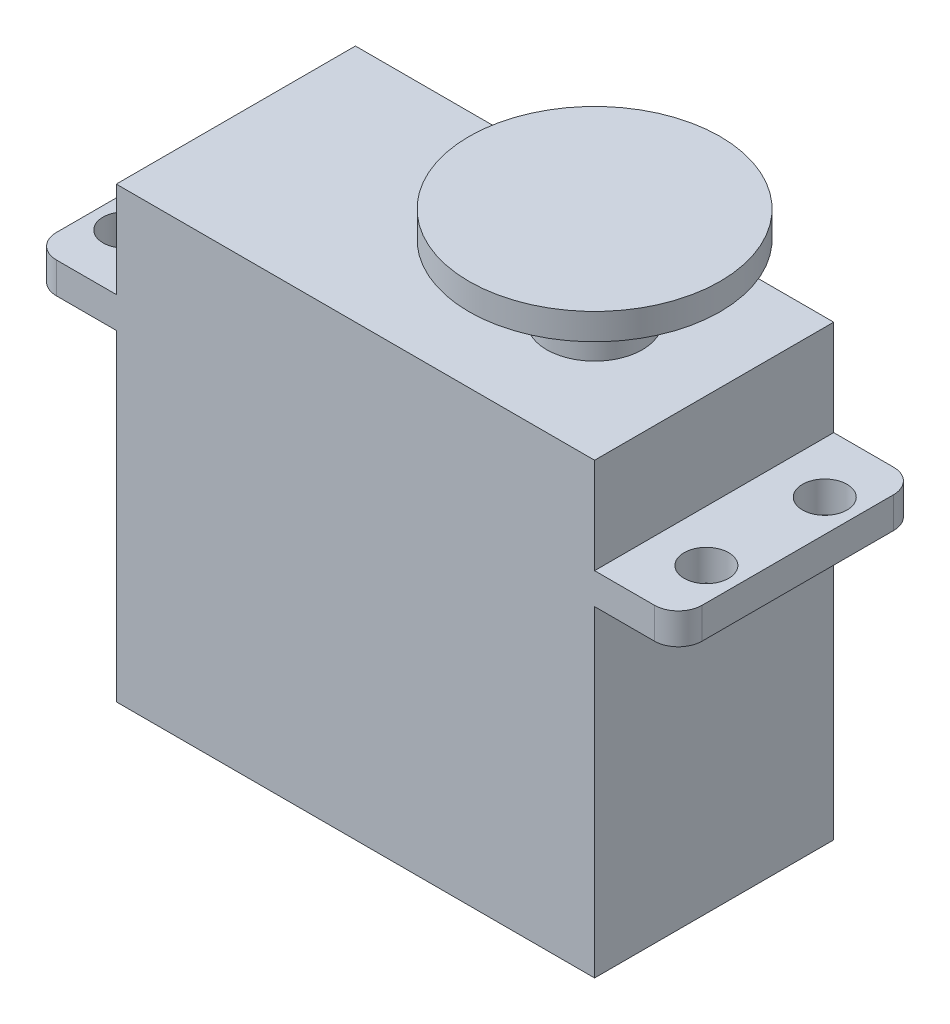
SolidWorks part; units mm, degrees
material "CA"
ref_plane "前视基准面" through (0, 0, 0) normal (0, 0, 1) x (1, 0, 0)
ref_plane "上视基准面" through (0, 0, 0) normal (0, 1, 0) x (1, 0, 0)
ref_plane "右视基准面" through (0, 0, 0) normal (1, 0, 0) x (0, 0, -1)
sketch "草图1" plane through (0, 0, 0) normal (0, 1, 0) x (1, 0, 0)
  line L1 (-30, 10) -> (10, 10)
  line L2 (-30, 10) -> (-30, -10)
  line L3 (-30, -10) -> (10, -10)
  line L4 (10, 10) -> (10, -10)
  line L5 (-30, 10) -> (10, -10) construction
  line L6 (-30, -10) -> (10, 10) construction
  point P0 (-10, 0)
  dimension "D1" = 10
  dimension "D2" = 40
  dimension "D3" = 20
extrude "凸台-拉伸1" add sketch "草图1" against normal blind 26.9
sketch "草图2" plane through (0, 0, 0) normal (0, 1, 0) x (1, 0, 0)
  line L5 (-35, -10) -> (15, -10)
  line L6 (-37, -8) -> (-37, 8)
  line L7 (-35, 10) -> (15, 10)
  line L8 (17, -8) -> (17, 8)
  line L9 (-37, -10) -> (17, 10) construction
  line L10 (-37, 10) -> (17, -10) construction
  circle A0 centre (-34.3, -4.95) radius 1.8638
  circle A1 centre (-34.3, 4.95) radius 1.8638
  circle A2 centre (14.3, -4.95) radius 1.8638
  circle A3 centre (14.3, 4.95) radius 1.8638
  arc A4 (15, 10) -> (17, 8) centre (15, 8) cw
  arc A5 (17, -8) -> (15, -10) centre (15, -8) cw
  arc A6 (-35, 10) -> (-37, 8) centre (-35, 8) ccw
  arc A7 (-35, -10) -> (-37, -8) centre (-35, -8) cw
  point P0 (-10, 0)
  point P1 (-10, 0)
  dimension "D8" = 2
  dimension "D1" = 10
  dimension "D2" = 54
  dimension "D3" = 20
  dimension "D4" = 4.95
  dimension "D5" = 9.9
  dimension "D6" = 24.3
  dimension "D7" = 48.6
extrude "凸台-拉伸2" add sketch "草图2" along normal blind 2.6
sketch "草图3" plane through (0, 2.6, 0) normal (0, 1, 0) x (1, 0, 0)
  line L0 (-35, -10) -> (15, -10) construction
  line L1 (-30, 10) -> (10, 10)
  line L2 (-30, 10) -> (-30, -10)
  line L3 (-30, -10) -> (10, -10)
  line L4 (10, 10) -> (10, -10)
  line L5 (-30, 10) -> (10, -10) construction
  line L6 (-30, -10) -> (10, 10) construction
  point P0 (-10, 0)
  dimension "D1" = 20
  dimension "D2" = 40
  dimension "D3" = 10
extrude "凸台-拉伸3" add sketch "草图3" along normal blind 8
sketch "草图4" plane through (0, 10.6, 0) normal (0, 1, 0) x (1, 0, 0)
  circle A0 centre (0, 0) radius 4
extrude "凸台-拉伸4" add sketch "草图4" along normal blind 6
sketch "草图5" plane through (0, 16.6, 0) normal (0, 1, 0) x (1, 0, 0)
  circle A0 centre (0, 0) radius 10.5
extrude "凸台-拉伸5" add sketch "草图5" along normal blind 2.2
